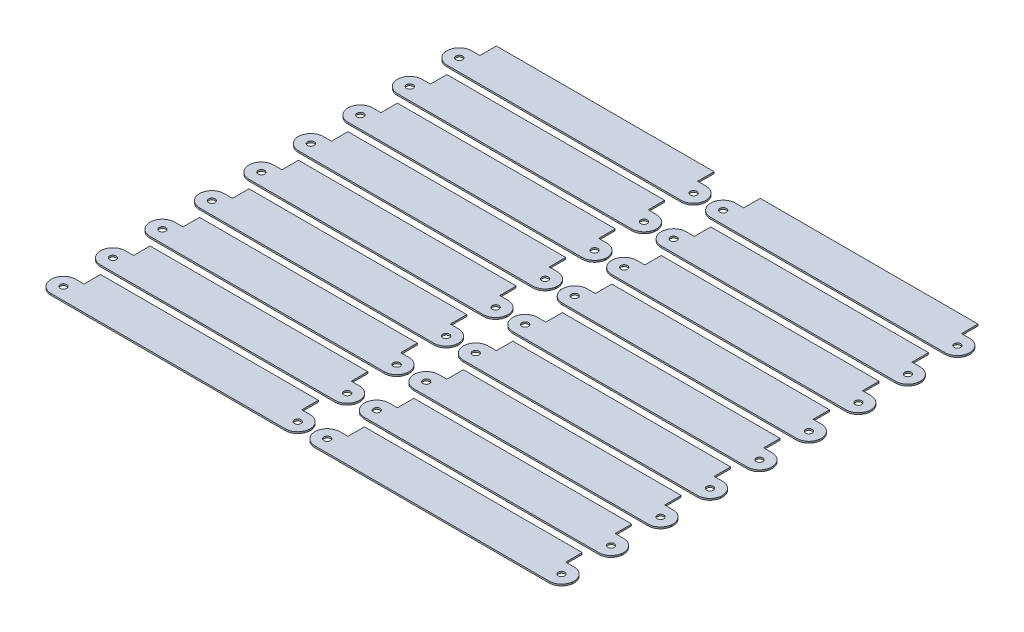
SolidWorks part; units mm, degrees
ref_plane "Front Plane" through (0, 0, 0) normal (0, 0, 1) x (1, 0, 0)
ref_plane "Top Plane" through (0, 0, 0) normal (0, 1, 0) x (1, 0, 0)
ref_plane "Right Plane" through (0, 0, 0) normal (1, 0, 0) x (0, 0, -1)
sketch "Sketch1" plane through (0, 0, 0) normal (0, 1, 0) x (1, 0, 0)
  line L0 (0, 0) -> (142.06, 0) construction
  line L1 (0, 7.5) -> (5, 7.5)
  line L2 (0, 7.5) -> (142.06, 7.5) construction
  line L3 (0, 7.5) -> (0, -7.5) construction
  line L4 (0, -7.5) -> (142.06, -7.5)
  line L5 (142.06, 7.5) -> (142.06, -7.5) construction
  line L6 (0, 7.5) -> (142.06, -7.5) construction
  line L7 (0, -7.5) -> (142.06, 7.5) construction
  line L8 (5, 7.5) -> (5, 17.5)
  line L9 (5, 17.5) -> (137.06, 17.5)
  line L10 (137.06, 17.5) -> (137.06, 7.5)
  line L11 (137.06, 7.5) -> (142.06, 7.5)
  line L12 (71.03, 0) -> (71.03, 17.5) construction
  line L17 (142.06, 0) -> (149.56, 0) construction
  line L19 (149.56, 1) -> (149.56, -1)
  line L20 (149.56, 1) -> (149.493, 1)
  line L21 (149.56, -1) -> (149.493, -1)
  line L32 (-7.5, 1) -> (-7.5, -1)
  line L33 (-7.5, -1) -> (-7.433, -1)
  line L44 (-7.5, 1) -> (-7.433, 1)
  circle A0 centre (0, 0) radius 2
  circle A1 centre (142.06, 0) radius 2
  arc A2 (0, 7.5) -> (0, -7.5) centre (0, 0) ccw construction
  arc A3 (142.06, -7.5) -> (142.06, 7.5) centre (142.06, 0) ccw construction
  arc A96 (0, 7.5) -> (-7.433, 1) centre (0, 0) ccw
  arc A97 (-7.433, -1) -> (0, -7.5) centre (0, 0) ccw
  arc A98 (149.493, 1) -> (142.06, 7.5) centre (142.06, 0) ccw
  arc A99 (149.493, -1) -> (142.06, -7.5) centre (142.06, 0) cw
  point P5 (71.03, 0)
  point P15 (-7.5, 0)
  dimension "D3" = 10
  dimension "D5" = 4
  dimension "D7" = 2
  dimension "D1" = 2
  dimension "D2" = 5
  dimension "D4" = 15
  dimension "D6" = 142.06
extrude "Boss-Extrude1" add sketch "Sketch1" along normal blind 1
pattern_linear "LPattern1" count 9 spacing 30 along (0, 0, -1) count 2 spacing 160 along (1, 0, 0) of bodies 101
